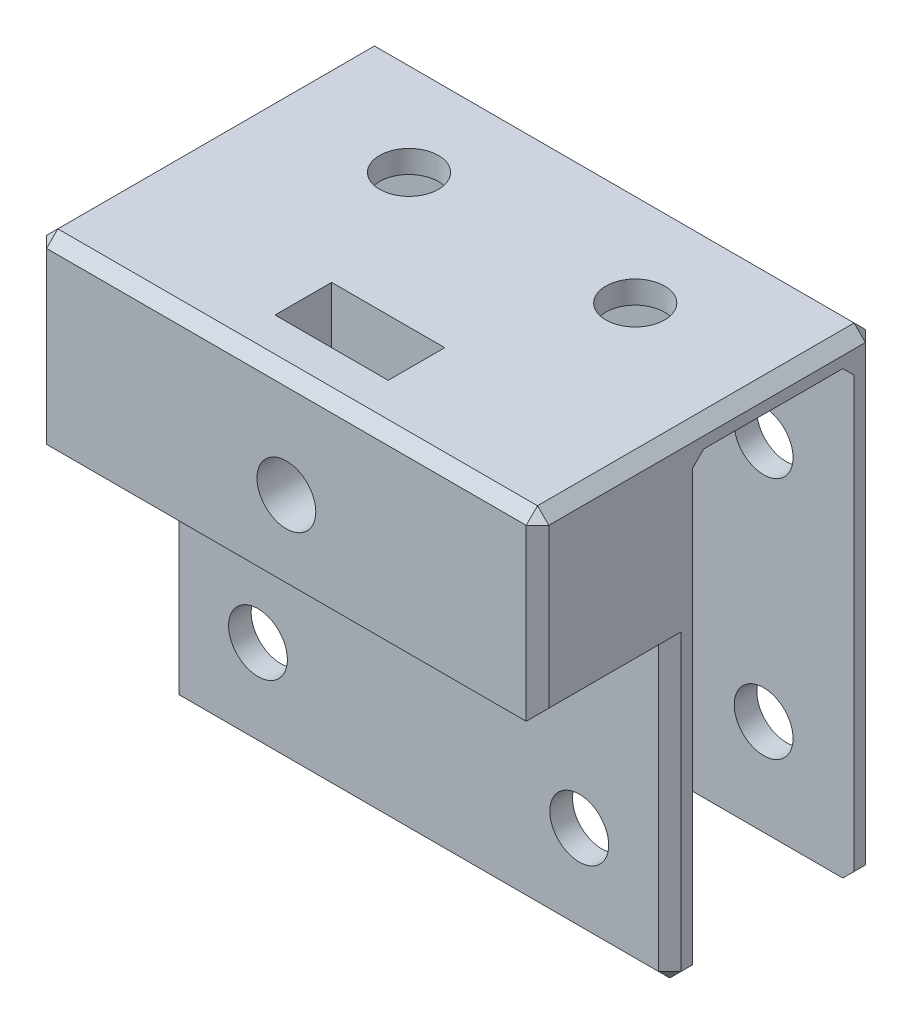
SolidWorks part; units mm, degrees
ref_plane "Front Plane" through (0, 0, 0) normal (0, 0, 1) x (1, 0, 0)
ref_plane "Top Plane" through (0, 0, 0) normal (0, 1, 0) x (1, 0, 0)
ref_plane "Right Plane" through (0, 0, 0) normal (1, 0, 0) x (0, 0, -1)
sketch "Sketch1" plane through (0, 0, 0) normal (0, 0, 1) x (1, 0, 0)
  line L0 (22.2, 40) -> (22.2, 0) construction
  line L1 (0, 0) -> (44.4, 0)
  line L2 (0, 0) -> (0, 40)
  line L3 (0, 40) -> (44.4, 40)
  line L4 (44.4, 0) -> (44.4, 40)
  line L5 (0, 0) -> (8, 0) construction
  line L6 (0, 0) -> (0, 8) construction
  line L10 (8, 29.9769) -> (8, 27.3769) construction
  line L11 (8, 19) -> (8, 8.4769) construction
  line L12 (8, 19) -> (10.573, 19) construction
  line L15 (10.573, 19) -> (10.573, 40) construction
  line L16 (8, 8.4769) -> (36.4, 8.4769) construction
  line L17 (36.4, 8.4769) -> (36.4, 29.9769) construction
  circle A0 centre (8, 8.4769) radius 2.6
  circle A1 centre (8, 29.9769) radius 2.6
  circle A2 centre (36.4, 29.9769) radius 2.6
  circle A3 centre (36.4, 8.4769) radius 2.6
  dimension "D5" = 5.2
  dimension "D6" = 5.2
  dimension "D7" = 5.2
  dimension "D8" = 5.2
  dimension "D1" = 44.4
  dimension "D2" = 40
  dimension "D3" = 21.5
  dimension "D4" = 21.5
  dimension "D9" = 21
  dimension "D10" = 8
  dimension "D11" = 8
extrude "Boss-Extrude1" add sketch "Sketch1" along normal blind 2
sketch "Sketch2" plane through (0, 40, 0) normal (0, 1, 0) x (1, 0, 0)
  line L0 (44.4, -2) -> (44.4, 0) construction
  line L1 (0, -2) -> (44.4, -2)
  line L2 (0, -2) -> (0, 16.3)
  line L3 (0, 16.3) -> (44.4, 16.3)
  line L4 (44.4, -2) -> (44.4, 16.3)
  dimension "D1" = 18.3
  dimension "D2" = 44.4
extrude "Boss-Extrude2" add sketch "Sketch2" along normal blind 2
pattern_linear "LPattern1" count 2 spacing 16.3 along (0, 0, -1) of "Boss-Extrude1"
sketch "Sketch3" plane through (0, 42, 0) normal (0, 1, 0) x (1, 0, 0)
  line L0 (22.2, 16.3) -> (22.2, -2) construction
  line L1 (44.4, 16.3) -> (0, 16.3) construction
  line L2 (0, -2) -> (44.4, -2) construction
  line L3 (22.2, 7.15) -> (12.2, 7.15) construction
  line L4 (22.2, 7.15) -> (32.2, 7.15) construction
  circle A0 centre (12.2, 7.15) radius 2.6
  circle A1 centre (32.2, 7.15) radius 2.6
  dimension "D3" = 5.2
  dimension "D4" = 5.2
  dimension "D1" = 10
  dimension "D2" = 10
extrude "Cut-Extrude1" cut sketch "Sketch3" against normal through all
sketch "Sketch5" plane through (0, 0, -16.3) normal (0, 0, -1) x (-1, 0, 0)
  line L1 (-22.2, 41) -> (-22.2, 34.93) construction
  dimension "D1" = 6.07
ref_plane "Plane1" through (22.2, 0, 0) normal (1, 0, 0) x (0, 0, -1)
sketch "Sketch6" plane through (22.2, 0, 0) normal (1, 0, 0) x (0, 0, -1)
  line L0 (16.3, 42) -> (-2, 42) construction
  line L1 (16.3, 41) -> (16.3, 34.93) construction
  line L3 (-2, 42) -> (-13.69, 42)
  line L4 (-13.69, 42) -> (-13.69, 26)
  line L5 (-13.69, 26) -> (-2, 26)
  line L6 (-2, 26) -> (-2, 42)
  dimension "D1" = 11.69
  dimension "D2" = 16
extrude "Boss-Extrude3" add sketch "Sketch6" along normal up to surface and the other way up to surface
fillet "Fillet4" radius 1 20 edges at (22.2, 40, -14.3) (22.2, 40, 0) (22.2, 0, -16.3) (22.2, 42, -16.3) (0, 0, 1) (0, 26, 7.845) (0, 42, -1.305) (0, 0, -15.3) (44.4, 0, -15.3) (44.4, 42, -1.305) (44.4, 26, 7.845) (44.4, 0, 1) (44.4, 13, 2) (44.4, 21, -16.3) (0, 21, -16.3) (0, 13, 2) (22.2, 0, 2) (22.2, 42, 13.69) (44.4, 34, 13.69) (0, 34, 13.69) profile chamfer
sketch "Sketch11" plane through (0, 42, 0) normal (0, 1, 0) x (1, 0, 0)
  line L1 (17.2, -9.69) -> (27.2, -9.69)
  line L2 (17.2, -9.69) -> (17.2, -4.69)
  line L3 (17.2, -4.69) -> (27.2, -4.69)
  line L4 (27.2, -9.69) -> (27.2, -4.69)
extrude "Cut-Extrude6" cut sketch "Sketch11" against normal offset from surface (14 mm away) 2 up to face at (22.2, 26, 7.845)
sketch "Sketch12" plane through (0, 26, 0) normal (0, -1, 0) x (1, 0, 0)
  line L1 (3, 2) -> (13, 2)
  line L2 (3, 2) -> (3, 10.3844)
  line L3 (3, 10.3844) -> (13, 10.3844)
  line L4 (41.4, 2) -> (41.4, 10.3844)
  line L6 (1, 13.69) -> (1, 2) construction
  line L7 (31.4, 10.3844) -> (31.4, 2)
  line L10 (43.4, 2) -> (43.4, 13.69) construction
  line L11 (3, 10.3844) -> (13, 10.3844)
  line L12 (3, 10.3844) -> (3, 2)
  line L13 (3, 2) -> (13, 2)
  line L14 (13, 10.3844) -> (13, 2)
  line L15 (31.4, 10.3844) -> (41.4, 10.3844)
  line L16 (31.4, 2) -> (41.4, 2)
  line L17 (43.4, 2) -> (1, 2) construction
  dimension "D1" = 2
  dimension "D2" = 2
  dimension "D4" = 10
  dimension "D5" = 10
extrude "Cut-Extrude7" cut sketch "Sketch12" against normal offset from surface (11 mm away) 5
sketch "Sketch7" plane through (0, 0, 13.69) normal (0, 0, 1) x (1, 0, 0)
  line L0 (22.2, 32.73) -> (22.2, 42) construction
  line L1 (44.4, 42) -> (0, 42) construction
  circle A0 centre (22.2, 32.73) radius 2.6
  dimension "D2" = 5.2
  dimension "D1" = 9.27
extrude "Cut-Extrude2" cut sketch "Sketch7" against normal up to surface (9 mm away) up to face at (22.2, 35, 4.69)
